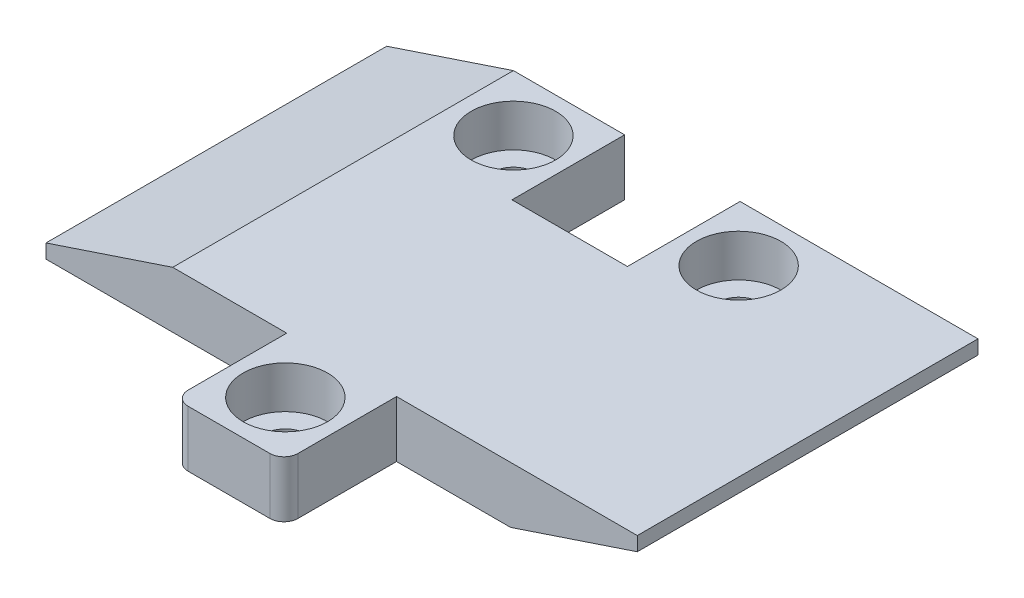
SolidWorks part; units mm, degrees
ref_plane "Front Plane" through (0, 0, 0) normal (0, 0, 1) x (1, 0, 0)
ref_plane "Top Plane" through (0, 0, 0) normal (0, 1, 0) x (1, 0, 0)
ref_plane "Right Plane" through (0, 0, 0) normal (1, 0, 0) x (0, 0, -1)
sketch "草图2" plane through (0, 0, 0) normal (0, 1, 0) x (1, 0, 0)
  line L0 (0, -1000) -> (0, 49000) construction
  line L1 (-8, -12.1) -> (8, -12.1) construction
  line L2 (-8, -12.1) -> (-8, 12.1) construction
  line L3 (-8, 12.1) -> (8, 12.1) construction
  line L4 (8, -12.1) -> (8, 12.1) construction
  line L5 (-8, -12.1) -> (8, 12.1) construction
  line L6 (-8, 12.1) -> (8, -12.1) construction
  line L7 (-19.5, -1001.2889) -> (-19.5, 48998.7111) construction
  line L8 (19.5, -1000.9497) -> (19.5, 48999.0503) construction
  circle A2 centre (-8, 12.1) radius 1.5
  circle A3 centre (8, 12.1) radius 1.5
  circle A4 centre (0, -12.1) radius 1.5
  point P0 (0, 0)
  dimension "D3" = 3
  dimension "D4" = 3
  dimension "D5" = 3
  dimension "D1" = 24.2
  dimension "D2" = 16
  dimension "D6" = 39
  dimension "D7" = 19.5
sketch "草图1" plane through (0, 0, 0) normal (0, 1, 0) x (1, 0, 0)
  line L0 (-21, 16.1) -> (-4.1, 16.1)
  line L1 (-4.1, 16.1) -> (-4.1, 8.1)
  line L2 (-4.1, 8.1) -> (4.1, 8.1)
  line L3 (4.1, 8.1) -> (4.1, 16.1)
  line L4 (4.1, 16.1) -> (21, 16.1)
  line L5 (21, 16.1) -> (21, -8.1)
  line L6 (21, -8.1) -> (3.9, -8.1)
  line L7 (3.9, -8.1) -> (3.9, -16.1)
  line L8 (3.9, -16.1) -> (-3.9, -16.1)
  line L9 (-3.9, -16.1) -> (-3.9, -8.1)
  line L10 (-3.9, -8.1) -> (-21, -8.1)
  line L11 (-21, -8.1) -> (-21, 16.1)
  line L12 (0, -2027.683) -> (0, 99356.4666) construction
  line L13 (-8, -12.1) -> (8, -12.1) construction
  line L14 (-8, 12.1) -> (8, 12.1) construction
  point P34 (-3.9, -12.1)
  point P37 (-4.1, 12.1)
  dimension "D1" = 42
  dimension "D2" = 7.8
  dimension "D3" = 8.2
  dimension "D4" = 8
  dimension "D5" = 8
extrude "凸台-拉伸1" add sketch "草图1" along normal blind 4
extrude "切除-拉伸2" cut sketch "草图2" along normal through all
sketch "草图3" plane through (0, 4, 0) normal (0, 1, 0) x (1, 0, 0)
  line L0 (-8, -12.1) -> (8, -12.1) construction
  circle A0 centre (-8, 12.1) radius 3
  circle A1 centre (8, 12.1) radius 3
  circle A2 centre (0, -12.1) radius 3
  dimension "D1" = 6
  dimension "D2" = 6
  dimension "D3" = 6
extrude "切除-拉伸3" cut sketch "草图3" against normal blind 3
sketch "草图4" plane through (0, 0, -16.1) normal (0, 0, -1) x (-1, 0, 0)
  line L0 (-21, 3) -> (-12, 0)
  line L1 (-21, 4) -> (-21, 0) construction
  line L2 (-21, 0) -> (-4.1, 0) construction
  line L3 (-12, 0) -> (-21, 0)
  line L4 (-21, 0) -> (-21, 3)
  line L5 (12, 4) -> (21, 1)
  line L6 (4.1, 4) -> (21, 4) construction
  line L7 (21, 4) -> (21, 0) construction
  line L8 (21, 1) -> (21, 4)
  line L9 (21, 4) -> (12, 4)
  dimension "D1" = 3
  dimension "D2" = 3
  dimension "D3" = 9
  dimension "D4" = 9
extrude "切除-拉伸4" cut sketch "草图4" against normal through all
fillet "圆角1" radius 1 2 edges at (3.9, 2, 16.1) (-3.9, 2, 16.1)
